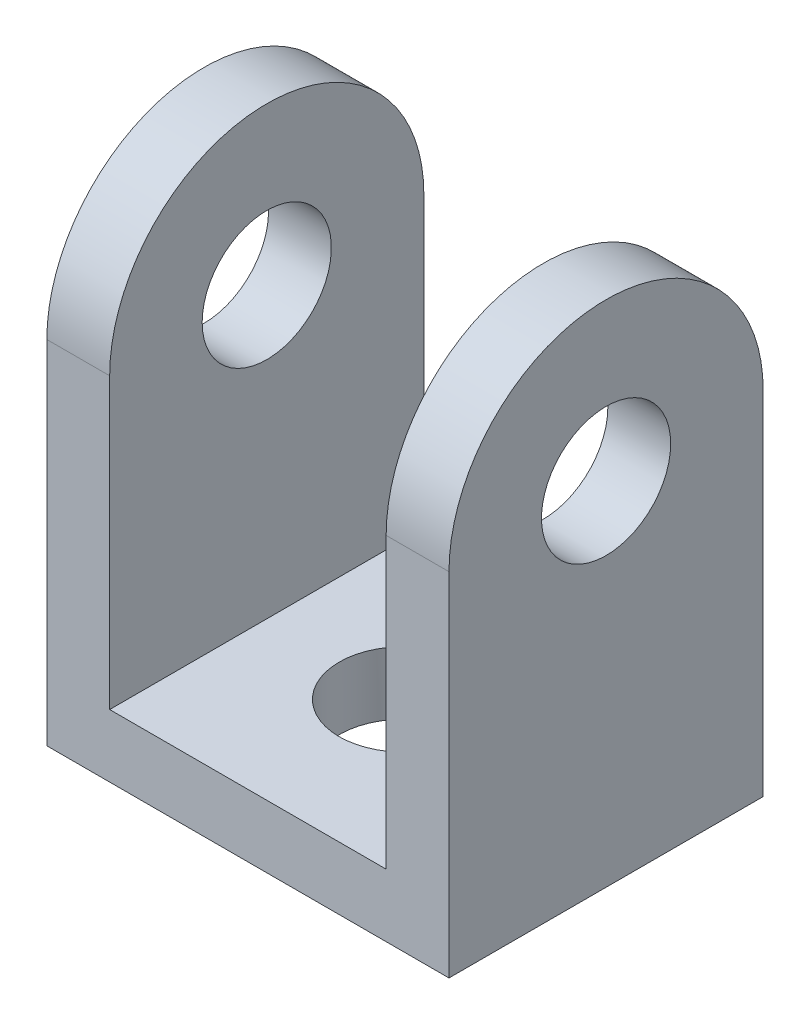
SolidWorks part; units mm, degrees
material "6061-T6 (SS)"
ref_plane "Front Plane" through (0, 0, 0) normal (0, 0, 1) x (1, 0, 0)
ref_plane "Top Plane" through (0, 0, 0) normal (0, 1, 0) x (1, 0, 0)
ref_plane "Right Plane" through (0, 0, 0) normal (1, 0, 0) x (0, 0, -1)
sketch "Sketch2" plane through (0, 0, 0) normal (1, 0, 0) x (0, 0, -1)
  line L0 (-7.9375, 0) -> (-7.9375, -17.78)
  line L1 (-7.9375, -17.78) -> (7.9375, -17.78)
  line L2 (7.9375, -17.78) -> (7.9375, 0)
  circle A0 centre (0, 0) radius 3.2639
  circle A1 centre (0, 0) radius 7.9375
  dimension "D1" = 6.5278
  dimension "D2" = 15.875
  dimension "D3" = 17.78
extrude "Boss-Extrude1" add sketch "Sketch2" along normal blind 20.32 contours A1 L0 L1 L2 | A1 A0
sketch "Sketch3" plane through (0, 0, 0) normal (0, 0, 1) x (1, 0, 0)
  line L1 (3.175, -14.605) -> (17.145, -14.605)
  line L2 (3.175, -14.605) -> (3.175, 10.795)
  line L3 (3.175, 10.795) -> (17.145, 10.795)
  line L4 (17.145, -14.605) -> (17.145, 10.795)
  line L5 (3.175, -14.605) -> (17.145, 10.795) construction
  line L6 (3.175, 10.795) -> (17.145, -14.605) construction
  line L8 (20.32, -17.78) -> (0, -17.78) construction
  line L9 (20.32, 0) -> (20.32, -17.78) construction
  line L11 (0, 0) -> (0, -17.78) construction
  point P0 (10.16, -1.905)
  dimension "D1" = 3.175
  dimension "D2" = 3.175
  dimension "D3" = 3.175
  dimension "D4" = 25.4
extrude "Cut-Extrude1" cut sketch "Sketch3" against normal mid plane 25.4
sketch "Sketch4" plane through (0, 0, 0) normal (0, 1, 0) x (1, 0, 0)
  line L0 (3.175, 7.9375) -> (17.145, 7.9375) construction
  circle A0 centre (10.16, -0.0635) radius 3.2639
  dimension "D3" = 6.5278
  dimension "D1" = 10.16
  dimension "D2" = 8.001
extrude "Cut-Extrude2" cut sketch "Sketch4" against normal through all
sketch3d "3DSketch1"
  line L0 (0, 0, 0) -> (20.32, 0, 0) construction
  line L1 (20.32, 0, 0) -> (17.145, 0, 0) construction
  line L2 (10.16, 0, 0) -> (10.16, 0, 7.1009) construction
  line L3 (10.16, 0, 0) -> (10.16, -7.9855, 0) construction
  line L4 (0.7251, 0, 0) -> (-8.7999, 0, 0) construction
